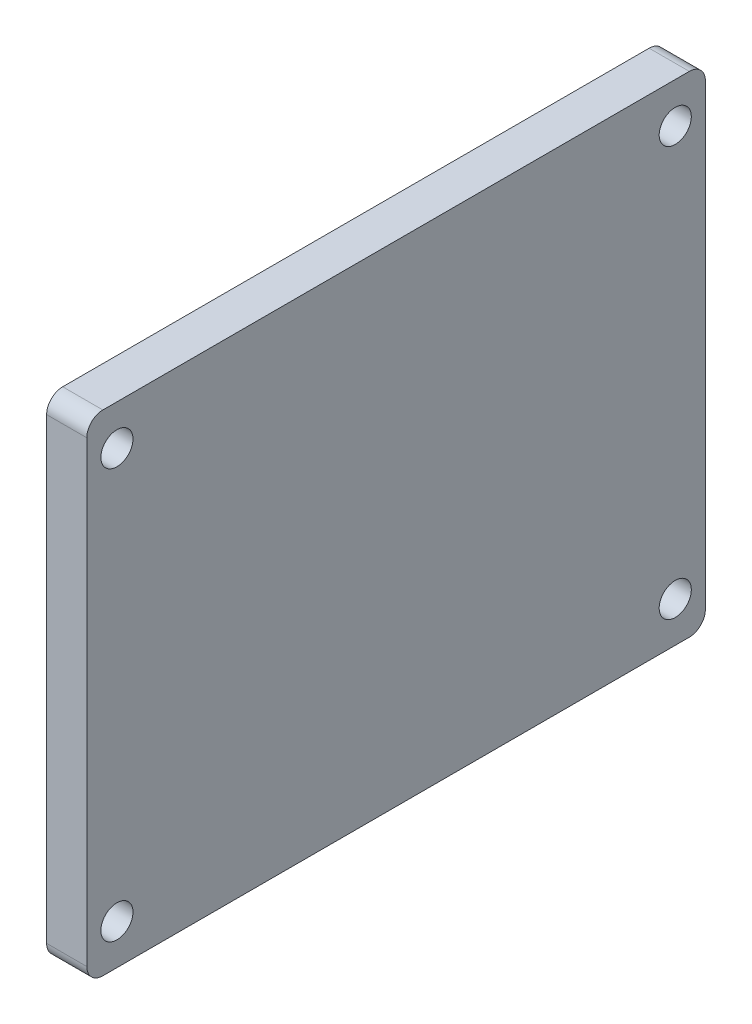
SolidWorks part; units mm, degrees
ref_plane "Alzado" through (0, 0, 0) normal (0, 0, 1) x (1, 0, 0)
ref_plane "Planta" through (0, 0, 0) normal (0, 1, 0) x (1, 0, 0)
ref_plane "Vista lateral" through (0, 0, 0) normal (1, 0, 0) x (0, 0, -1)
sketch "Croquis1" plane through (0, 0, 0) normal (1, 0, 0) x (0, 0, -1)
  line L1 (-38.5, 30.5) -> (38.5, 30.5)
  line L2 (-38.5, 30.5) -> (-38.5, -30.5)
  line L3 (-38.5, -30.5) -> (38.5, -30.5)
  line L4 (38.5, 30.5) -> (38.5, -30.5)
  line L5 (-38.5, 30.5) -> (38.5, -30.5) construction
  line L6 (-38.5, -30.5) -> (38.5, 30.5) construction
  point P0 (0, 0)
  dimension "D1" = 61
  dimension "D2" = 77
extrude "Saliente-Extruir1" add sketch "Croquis1" along normal blind 5
sketch "Croquis2" plane through (5, 0, 0) normal (1, 0, 0) x (0, 0, -1)
  line L0 (38.5, 30.5) -> (-38.5, 30.5) construction
  line L1 (-38.5, 30.5) -> (-38.5, -30.5) construction
  line L2 (-38.5, -30.5) -> (38.5, -30.5) construction
  line L3 (38.5, -30.5) -> (38.5, 30.5) construction
  circle A0 centre (-34.75, 25.5) radius 2
  circle A1 centre (-34.75, -25.5) radius 2
  circle A2 centre (34.75, 25.5) radius 2
  circle A3 centre (34.75, -25.5) radius 2
  dimension "D1" = 4
  dimension "D4" = 4
  dimension "D6" = 4
  dimension "D8" = 4
  dimension "D2" = 5
  dimension "D3" = 3.75
  dimension "D5" = 5
  dimension "D7" = 3.75
  dimension "D9" = 5
  dimension "D10" = 5
extrude "Cortar-Extruir1" cut sketch "Croquis2" against normal blind 5
fillet "Redondeo2" radius 2 1 edges at (2.5, 30.5, 38.5)
fillet "Redondeo3" radius 2 1 edges at (2.5, 30.5, -38.5)
fillet "Redondeo4" radius 2 2 edges at (2.5, -30.5, 38.5) (2.5, -30.5, -38.5)
